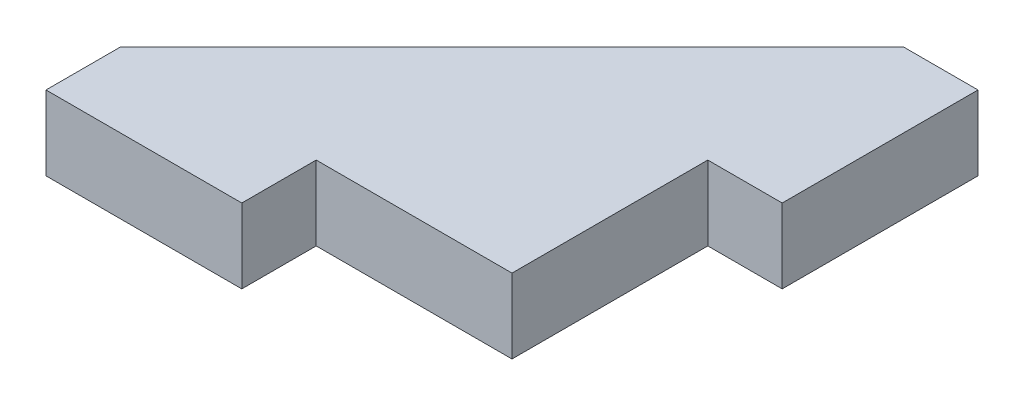
SolidWorks part; units mm, degrees
ref_plane "Front Plane" through (0, 0, 0) normal (0, 0, 1) x (1, 0, 0)
ref_plane "Top Plane" through (0, 0, 0) normal (0, 1, 0) x (1, 0, 0)
ref_plane "Right Plane" through (0, 0, 0) normal (1, 0, 0) x (0, 0, -1)
sketch "Sketch1" plane through (0, 0, 0) normal (0, 1, 0) x (1, 0, 0)
  line L0 (-21.062, -13.6221) -> (4.338, 11.7779)
  line L2 (4.338, 11.7779) -> (9.164, 11.7779)
  line L3 (-21.062, -13.6221) -> (4.338, -13.6221)
  line L4 (4.338, 11.7779) -> (4.338, -13.6221)
  line L5 (4.338, 11.7779) -> (4.338, -0.9221)
  line L6 (4.338, -0.9221) -> (9.164, -0.9221)
  line L7 (9.164, 11.7779) -> (9.164, -0.9221)
  line L8 (-21.062, -13.6221) -> (-8.362, -13.6221)
  line L9 (-21.062, -13.6221) -> (-21.062, -18.4481)
  line L10 (-21.062, -18.4481) -> (-8.362, -18.4481)
  line L11 (-8.362, -13.6221) -> (-8.362, -18.4481)
  dimension "D2" = 25.4
  dimension "D1" = 12.7
  dimension "D3" = 12.7
  dimension "D4" = 4.826
  dimension "D5" = 4.826
extrude "Boss-Extrude1" add sketch "Sketch1" along normal blind 4.826 contours L11 L3 L9 L10 | L4 L0 L3 | L7 L2 L4 L6
equation "\"MDF\"= 0.19in"
equation "\"Foamcore\"= .13in"
equation "\"Gmaterial\"= \"MDF\""
equation "\"D4@Sketch1\"=\"MDF\""
equation "\"D5@Sketch1\"=\"MDF\""
equation "\"D1@Boss-Extrude1\"=\"MDF\""
equation "\"PVCID\" = 2.067in"
equation "\"PVCOD\" = 2.375in"
equation "\"GenDiameter\"= 60mm"
equation "\"GenCutDiameter\" = 1.8in"
equation "\"GenCutDistance\" = 1"
equation "\"TowerHeight\" = 6in"
equation "\"TowerFrontBase\" = 3in"
equation "\"FunnelHeight\" = 1in"
equation "\"FunnelAngle\" = 20"
equation "\"TowerSideBase\" = 3in"
equation "\"TowerPanelLength\" = 2in"
equation "\"TowerPanelLeeway\" = 0.5in"
equation "\"BaseLength\" = 9in"
equation "\"BaseWidth\" = 10in"
equation "\"WheelHoleLength\" = 3.25in"
equation "\"WheelHoleWidth\" = 26mm"
equation "\"WheelHoleFromBack\" = 1in"
equation "\"DropLength\" = 1in"
equation "\"DropWidth\" = 8.5in"
equation "\"BumperWidth\" = 1in"
equation "\"HoleDiameter\"= 0.25in"
equation "\"SmallHexDiameter\" = 0.185in"
equation "\"SmallHexHeight\" = 0.701in"
equation "\"ScrewSize\" = 0.106in"
equation "\"BigHexDiameter\" = 0.251in"
equation "\"BigHexHeight\" = 0.374in"
equation "\"PCBThickness\" = 0.066in"
equation "\"ConnectorHeight\" = 0.517in"
equation "\"BoardHeight\" = 0.583in"
equation "\"UnoStackHeight\" = 1.351in"
equation "\"UnoStackWidth\" = 3.053in"
equation "\"UnoStackLength\" = 3.152in"
equation "\"HBridgeWidth\" = 1.797in"
equation "\"HBridgeLength\" = 2.236in"
equation "\"DSWidth\" = 1.820in"
equation "\"DSLength\" = 1.833in"
equation "\"StepperWidth\" = 1.799in"
equation "\"StepperLength\" = 2.248in"
equation "\"ULNWidth\" = 1.304in"
equation "\"ULNLength\" = 1.545in"
equation "\"VSwitchHeight\" = 0.392in"
equation "\"VSwitchWidth\" = 0.637in"
equation "\"VSwitchLength\" = 1.097in"
equation "\"SkateWheelDiameter\" = 80mm"
equation "\"SkateWheelThickness\" = 24mm"
equation "\"BaseDistance\" = 3in"
